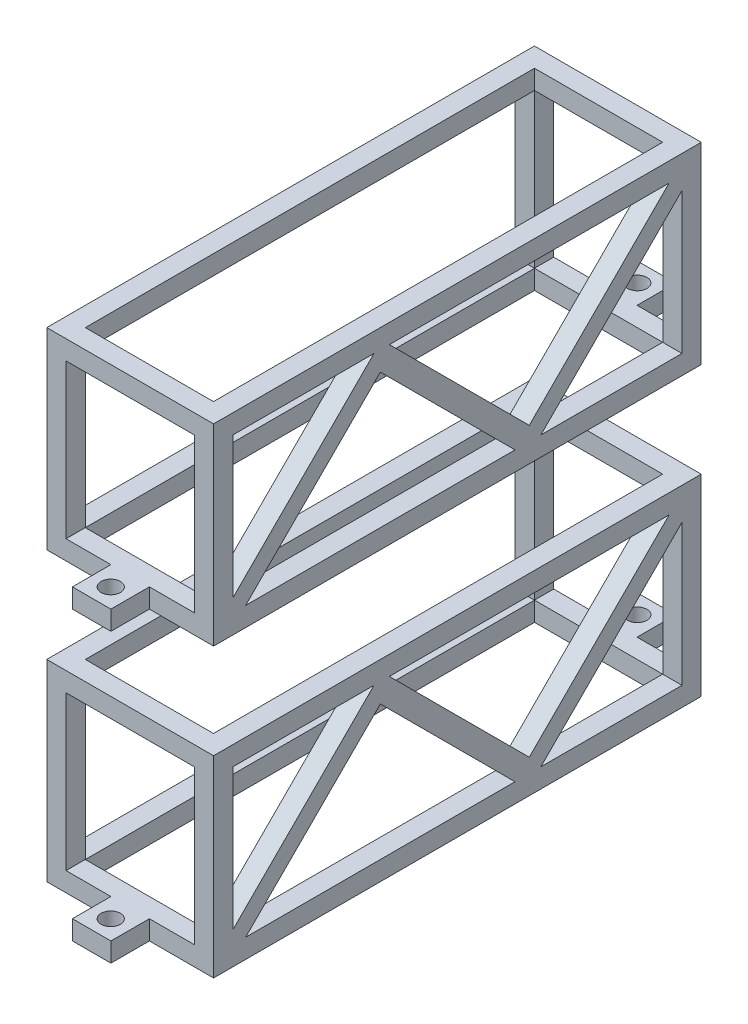
SolidWorks part; units mm, degrees
ref_plane "Front Plane" through (0, 0, 0) normal (0, 0, 1) x (1, 0, 0)
ref_plane "Top Plane" through (0, 0, 0) normal (0, 1, 0) x (1, 0, 0)
ref_plane "Right Plane" through (0, 0, 0) normal (1, 0, 0) x (0, 0, -1)
sketch "Sketch1" plane through (0, 0, 0) normal (0, 1, 0) x (1, 0, 0)
  line L1 (-6.1998, -22.4954) -> (-26.176, -22.4954)
  line L2 (-6.1998, -22.4954) -> (-6.1998, 47.5114)
  line L3 (-6.1998, 47.5114) -> (-26.176, 47.5114)
  line L4 (-26.176, -22.4954) -> (-26.176, 47.5114)
  line L5 (-6.1998, -22.4954) -> (-26.176, 47.5114) construction
  line L6 (-6.1998, 47.5114) -> (-26.176, -22.4954) construction
  line L7 (-3.1903, -25.4928) -> (-29.1855, -25.4928)
  line L8 (-3.1903, -25.4928) -> (-3.1903, 50.5088)
  line L9 (-3.1903, 50.5088) -> (-29.1855, 50.5088)
  line L10 (-29.1855, -25.4928) -> (-29.1855, 50.5088)
  line L11 (-3.1903, -25.4928) -> (-29.1855, 50.5088) construction
  line L12 (-3.1903, 50.5088) -> (-29.1855, -25.4928) construction
  point P0 (-16.1879, 12.508)
  point P5 (-16.1879, 12.508)
  dimension "D1" = 0
extrude "Boss-Extrude2" add sketch "Sketch1" along normal blind 30
sketch "Sketch2" plane through (0, 0, 25.4928) normal (0, 0, 1) x (1, 0, 0)
  line L0 (-29.1855, 30) -> (-3.1903, 30) construction
  line L1 (-6.1855, 3) -> (-26.1855, 3)
  line L2 (-6.1855, 3) -> (-6.1855, 27)
  line L3 (-6.1855, 27) -> (-26.1855, 27)
  line L4 (-26.1855, 3) -> (-26.1855, 27)
  line L5 (-6.1855, 3) -> (-26.1855, 27) construction
  line L6 (-6.1855, 27) -> (-26.1855, 3) construction
  line L7 (-29.1855, 30) -> (-29.1855, 0) construction
  point P0 (-16.1855, 15)
  dimension "D1" = 3
  dimension "D2" = 3
  dimension "D3" = 20
extrude "Cut-Extrude1" cut sketch "Sketch2" against normal through all both and the other way through all
sketch "Sketch3" plane through (-29.1855, 0, 0) normal (-1, 0, 0) x (0, 0, 1)
  line L0 (25.4928, 30) -> (25.4928, 0) construction
  line L1 (22.4928, 3) -> (-47.5072, 3)
  line L2 (22.4928, 3) -> (22.4928, 27)
  line L3 (22.4928, 27) -> (-47.5072, 27)
  line L4 (-47.5072, 3) -> (-47.5072, 27)
  line L5 (22.4928, 3) -> (-47.5072, 27) construction
  line L6 (22.4928, 27) -> (-47.5072, 3) construction
  line L7 (-50.5088, 30) -> (25.4928, 30) construction
  line L9 (-50.5088, 0) -> (25.4928, 0) construction
  point P0 (-12.5072, 15)
  dimension "D1" = 3
  dimension "D2" = 3
  dimension "D3" = 3
extrude "Cut-Extrude2" cut sketch "Sketch3" against normal through all both and the other way through all
sketch "Sketch5" plane through (0, 0, 0) normal (0, -1, 0) x (-1, 0, 0)
  line L0 (29.1855, -25.4928) -> (3.1903, -25.4928) construction
  line L1 (19.1903, -31.4928) -> (13.1903, -31.4928)
  line L2 (19.1903, -31.4928) -> (19.1903, -25.4928)
  line L3 (19.1903, -25.4928) -> (13.1903, -25.4928)
  line L4 (13.1903, -31.4928) -> (13.1903, -25.4928)
  line L5 (19.1903, -31.4928) -> (13.1903, -25.4928) construction
  line L6 (19.1903, -25.4928) -> (13.1903, -31.4928) construction
  line L7 (13.1903, 56.5088) -> (19.1903, 56.5088)
  line L8 (13.1903, 56.5088) -> (13.1903, 50.5088)
  line L9 (13.1903, 50.5088) -> (19.1903, 50.5088)
  line L10 (19.1903, 56.5088) -> (19.1903, 50.5088)
  line L11 (13.1903, 56.5088) -> (19.1903, 50.5088) construction
  line L12 (13.1903, 50.5088) -> (19.1903, 56.5088) construction
  line L13 (3.1903, 50.5088) -> (29.1855, 50.5088) construction
  line L14 (3.1903, -25.4928) -> (3.1903, 50.5088) construction
  circle A0 centre (16.1903, 53.5429) radius 1.5
  circle A1 centre (16.1903, -28.5167) radius 1.5
  point P0 (16.1903, -28.4928)
  point P5 (16.1903, 53.5088)
  dimension "D5" = 3
  dimension "D6" = 3
  dimension "D1" = 0
  dimension "D2" = 0
  dimension "D3" = 13
  dimension "D4" = 13
extrude "Boss-Extrude3" add sketch "Sketch5" against normal blind 3
sketch "Sketch7" plane through (-3.1903, 0, 0) normal (1, 0, 0) x (0, 0, -1)
  line L0 (47.5072, 25) -> (23.4976, 0.9904)
  line L1 (23.4976, 0.9904) -> (0.4976, 23.9904)
  line L2 (0.4976, 23.9904) -> (-20.4928, 3)
  line L3 (-20.4928, 3) -> (-22.4928, 3)
  line L4 (-22.4928, 3) -> (-22.4928, 5)
  line L5 (-22.4928, 5) -> (-0.4928, 27)
  line L6 (-0.4928, 27) -> (1.5072, 27)
  line L7 (1.5072, 27) -> (1.9072, 27)
  line L8 (1.9072, 27) -> (23.7072, 5.2)
  line L9 (23.7072, 5.2) -> (45.5072, 27)
  line L10 (45.5072, 27) -> (47.5072, 27)
  line L11 (47.5072, 27) -> (47.5072, 25)
  line L12 (-22.4928, 3) -> (-22.4928, 27) construction
  line L13 (47.5072, 3) -> (-22.4928, 3) construction
  line L14 (-22.4928, 27) -> (47.5072, 27) construction
  line L15 (47.5072, 27) -> (47.5072, 3) construction
  dimension "D1" = 0
  dimension "D2" = 0
  dimension "D3" = 0
  dimension "D4" = 0
  dimension "D5" = 45
  dimension "D6" = 45
  dimension "D7" = 2
  dimension "D8" = 2
  dimension "D9" = 0
  dimension "D10" = 135
  dimension "D11" = 0
  dimension "D12" = 2.8284
  dimension "D14" = 0
  dimension "D15" = 0
  dimension "D17" = 0
  dimension "D18" = 0
  dimension "D19" = 0
  dimension "D22" = 135
  dimension "D23" = 135
  dimension "D24" = 45
  dimension "D25" = 45
extrude "Boss-Extrude7" add sketch "Sketch7" against normal blind 3
move or copy body "Body-Move/Copy2" bodies to move or copy 110 copy yes number of copies 1 translate (0, 44.7888, 0) parameters "D1"=0, "D2"=44.7888, "D3"=0
